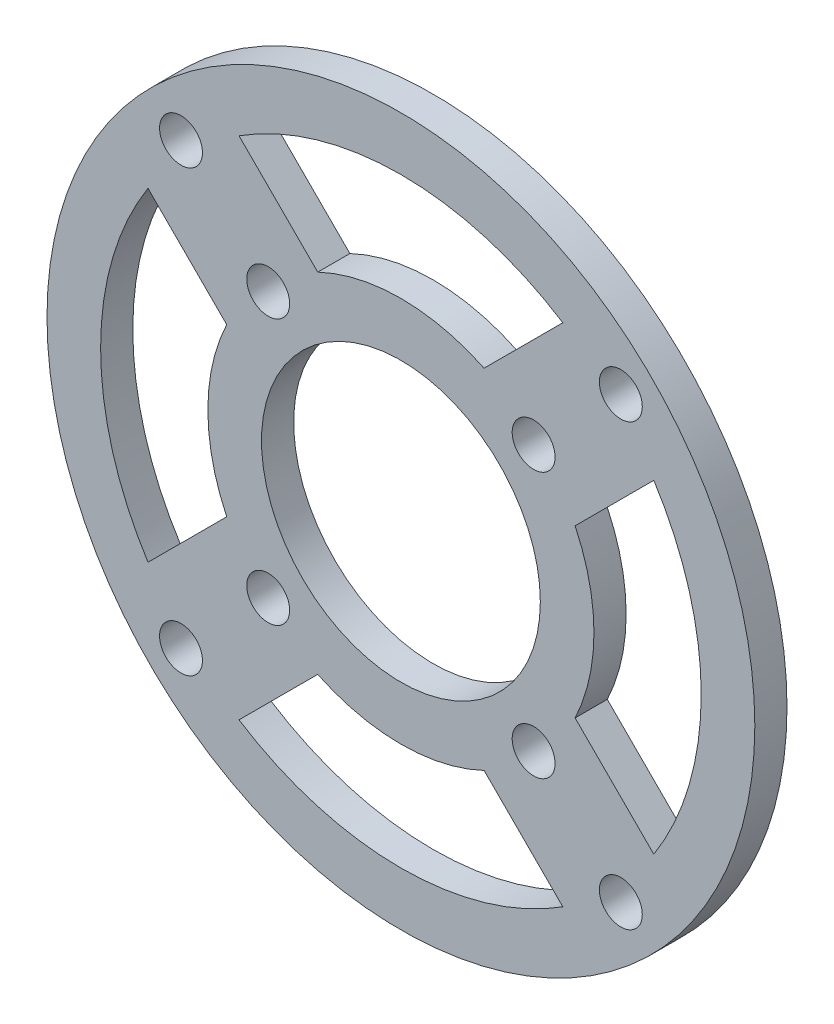
SolidWorks part; units mm, degrees
material "6061 合金"
ref_plane "前视基准面" through (0, 0, 0) normal (0, 0, 1) x (1, 0, 0)
ref_plane "上视基准面" through (0, 0, 0) normal (0, 1, 0) x (1, 0, 0)
ref_plane "右视基准面" through (0, 0, 0) normal (1, 0, 0) x (0, 0, -1)
sketch "草图1" plane through (0, 0, 0) normal (0, 0, 1) x (1, 0, 0)
  line L0 (0, 36.4689) -> (0, -50.0879) construction
  line L1 (0, 0) -> (-20.535, 20.535) construction
  circle A0 centre (0, 0) radius 33
  circle A2 centre (-20.5061, 20.5061) radius 2
  circle A3 centre (20.5061, 20.5061) radius 2
  circle A4 centre (20.5061, -20.5061) radius 2
  circle A5 centre (-20.5061, -20.5061) radius 2
  circle A7 centre (-12.3744, 12.3744) radius 2
  circle A8 centre (12.3744, 12.3744) radius 2
  circle A9 centre (12.3744, -12.3744) radius 2
  circle A10 centre (-12.3744, -12.3744) radius 2
  circle A11 centre (0, 0) radius 13
  point P17 (0, 0)
  point P26 (0, 0)
  dimension "D1" = 66
  dimension "D2" = 4
  dimension "D4" = 29
  dimension "D6" = 4
  dimension "D7" = 17.5
  dimension "D9" = 26
  dimension "D3" = 45
  dimension "D5" = 4
  dimension "D8" = 4
extrude "凸台-拉伸1" add sketch "草图1" along normal blind 3
sketch "草图2" plane through (0, 0, 3) normal (0, 0, 1) x (1, 0, 0)
  line L0 (0, 0) -> (-20.5061, 20.5061) construction
  line L1 (-7.7574, 16.2426) -> (-15.0964, 23.5817)
  line L2 (0, 0) -> (20.5061, 20.5061) construction
  line L3 (7.7574, 16.2426) -> (15.0964, 23.5817)
  line L4 (0, 0) -> (0, 35.6215) construction
  line L5 (16.2426, 7.7574) -> (23.5817, 15.0964)
  line L6 (16.2426, -7.7574) -> (23.5817, -15.0964)
  line L7 (7.7574, -16.2426) -> (15.0964, -23.5817)
  line L8 (-7.7574, -16.2426) -> (-15.0964, -23.5817)
  line L9 (-16.2426, -7.7574) -> (-23.5817, -15.0964)
  line L10 (-16.2426, 7.7574) -> (-23.5817, 15.0964)
  arc A0 (15.0964, 23.5817) -> (-15.0964, 23.5817) centre (0, 0) ccw
  arc A1 (7.7574, 16.2426) -> (-7.7574, 16.2426) centre (0, 0) ccw
  circle A2 centre (-12.3744, 12.3744) radius 2 construction
  circle A3 centre (0, 0) radius 13 construction
  circle A4 centre (0, 0) radius 33 construction
  arc A5 (16.2426, -7.7574) -> (16.2426, 7.7574) centre (0, 0) ccw
  arc A6 (23.5817, -15.0964) -> (23.5817, 15.0964) centre (0, 0) ccw
  arc A7 (-7.7574, -16.2426) -> (7.7574, -16.2426) centre (0, 0) ccw
  arc A8 (-15.0964, -23.5817) -> (15.0964, -23.5817) centre (0, 0) ccw
  arc A9 (-16.2426, 7.7574) -> (-16.2426, -7.7574) centre (0, 0) ccw
  arc A10 (-23.5817, 15.0964) -> (-23.5817, -15.0964) centre (0, 0) ccw
  point P32 (0, 0)
  dimension "D2" = 5
  dimension "D3" = 5
  dimension "D1" = 6
  dimension "D4" = 4
extrude "切除-拉伸1" cut sketch "草图2" against normal through all
sketch "草图3" [suppressed] plane through (0, 0, 3) normal (0, 0, 1) x (1, 0, 0)
  line L2 (0, 0) -> (0, 22.3055) construction
  line L3 (-6, 13.7477) -> (-6, 11.5326)
  line L4 (6, 13.7477) -> (6, 11.5326)
  line L6 (13.7477, 6) -> (11.5326, 6)
  line L7 (13.7477, -6) -> (11.5326, -6)
  line L8 (6, -13.7477) -> (6, -11.5326)
  line L9 (-6, -13.7477) -> (-6, -11.5326)
  line L10 (-13.7477, -6) -> (-11.5326, -6)
  line L11 (-13.7477, 6) -> (-11.5326, 6)
  arc A1 (13.7477, -6) -> (13.7477, 6) centre (0, 0) ccw
  arc A9 (6, 13.7477) -> (-6, 13.7477) centre (0, 0) ccw
  circle A10 centre (0, 0) radius 13 construction
  arc A11 (6, 11.5326) -> (-6, 11.5326) centre (0, 0) ccw
  arc A12 (11.5326, -6) -> (11.5326, 6) centre (0, 0) ccw
  arc A13 (-6, -13.7477) -> (6, -13.7477) centre (0, 0) ccw
  arc A14 (-6, -11.5326) -> (6, -11.5326) centre (0, 0) ccw
  arc A15 (-13.7477, 6) -> (-13.7477, -6) centre (0, 0) ccw
  arc A16 (-11.5326, 6) -> (-11.5326, -6) centre (0, 0) ccw
  point P22 (0, 0)
  dimension "D2" = 2
  dimension "D1" = 12
extrude "凸台-拉伸2" [suppressed] add sketch "草图3" along normal blind 2
